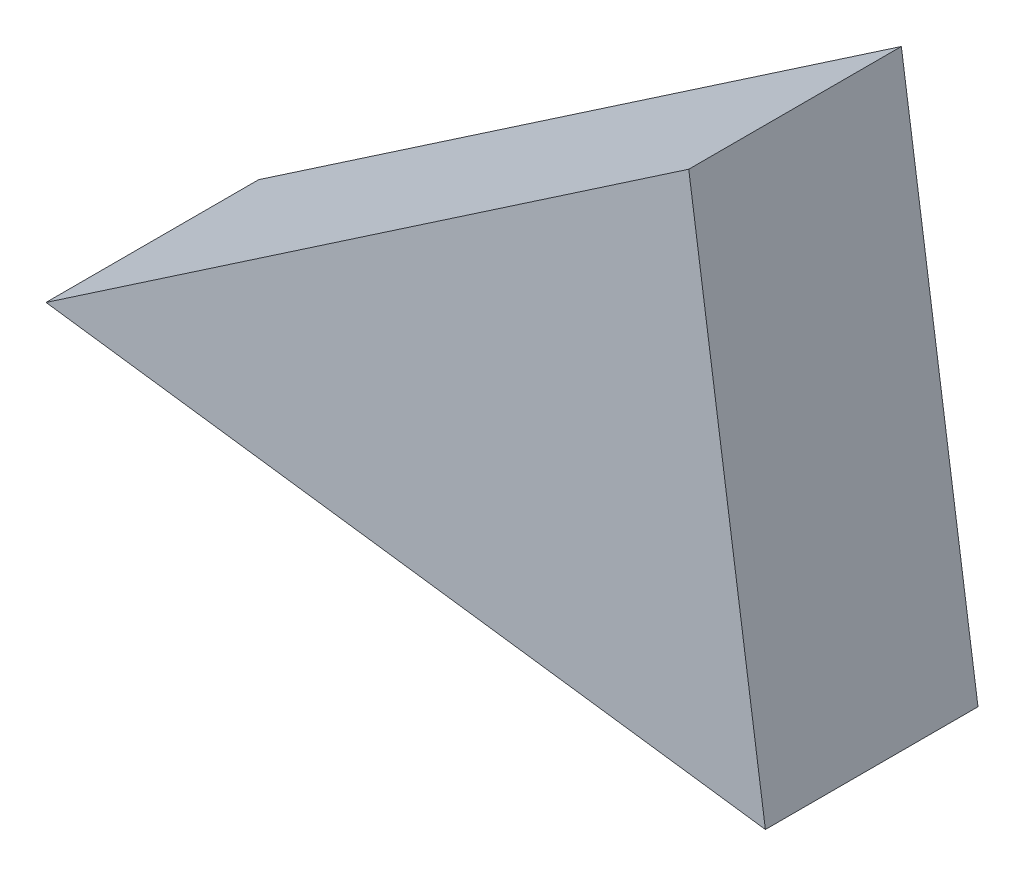
SolidWorks part; units mm, degrees
ref_plane "前视基准面" through (0, 0, 0) normal (0, 0, 1) x (1, 0, 0)
ref_plane "上视基准面" through (0, 0, 0) normal (0, 1, 0) x (1, 0, 0)
ref_plane "右视基准面" through (0, 0, 0) normal (1, 0, 0) x (0, 0, -1)
sketch "草图1" plane through (0, 0, 0) normal (0, 0, 1) x (1, 0, 0)
  line L0 (66.4509, 44.2876) -> (36.221, 23.747)
  line L1 (66.4509, 44.2876) -> (70.0559, 19.1948)
  line L2 (70.0559, 19.1948) -> (36.221, 23.747)
extrude "凸台-拉伸1" add sketch "草图1" along normal blind 10
